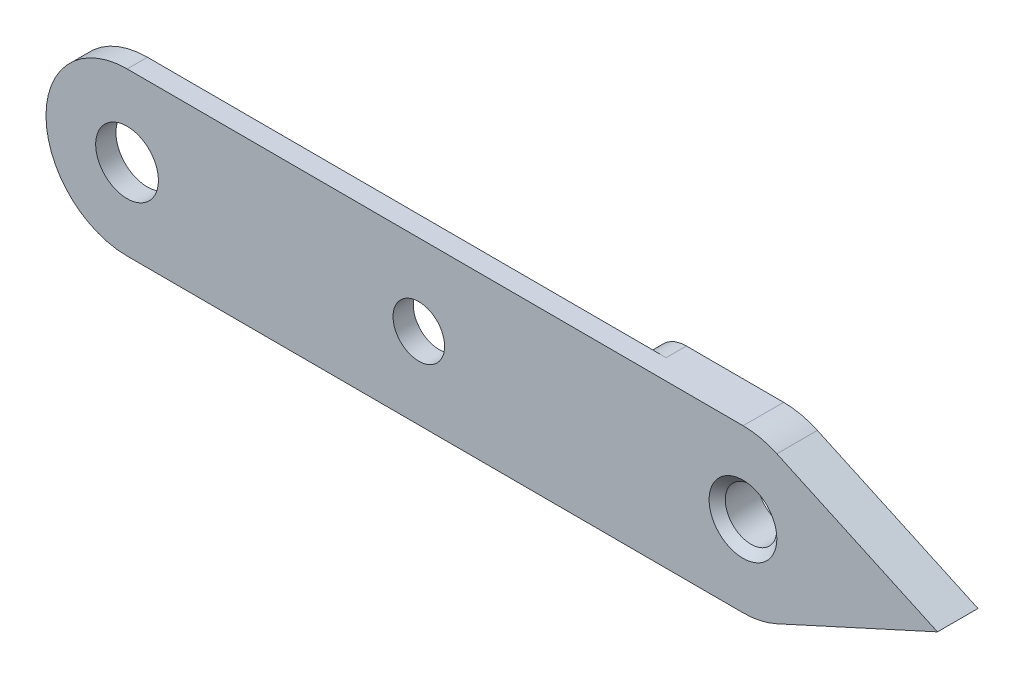
SolidWorks part; units mm, degrees
ref_plane "Front Plane" through (0, 0, 0) normal (0, 0, 1) x (1, 0, 0)
ref_plane "Top Plane" through (0, 0, 0) normal (0, 1, 0) x (1, 0, 0)
ref_plane "Right Plane" through (0, 0, 0) normal (1, 0, 0) x (0, 0, -1)
sketch "Sketch2" plane through (0, 0, -44.7) normal (0, 0, 1) x (1, 0, 0)
  line L0 (-22.86, 0.0379) -> (25.4, -0.0421) construction
  line L1 (-22.8705, -6.3121) -> (25.3894, -6.3921)
  line L2 (-22.8494, 6.3879) -> (25.4105, 6.3079)
  arc A0 (-22.8705, -6.3121) -> (-22.8494, 6.3879) centre (-22.86, 0.0379) cw
  arc A1 (25.3894, -6.3921) -> (25.4105, 6.3079) centre (25.4, -0.0421) ccw
  circle A2 centre (25.4, -0.0421) radius 0.635
  circle A3 centre (0, 0) radius 1.5875
  circle A4 centre (-22.86, 0.0379) radius 0.635
  dimension "D3" = 1.27
  dimension "D4" = 3.175
  dimension "D1" = 6.35
  dimension "D2" = 6.35
extrude "Boss-Extrude1" add sketch "Sketch2" along normal blind 1.5875
hole_wizard "#10 (0.1935) Diameter Hole1" positions "Sketch4" profile "Sketch3" hole size "#10" standard "ANSI Inch" end condition through all
sketch "Sketch4" plane through (0, 0, -43.1125) normal (0, 0, 1) x (1, 0, 0)
  point P0 (-22.86, 0.0379)
sketch "Sketch3" plane through (-22.86, 0.0379, -43.1125) normal (1, 0, 0) x (0, -1, 0)
  line L0 (0, 0) -> (0, 1.5875)
  line L1 (0, 1.5875) -> (2.4574, 1.5875)
  line L2 (2.4574, 1.5875) -> (2.4574, 0)
  line L5 (2.4574, 0) -> (0, 0)
  line L11 (0, -6.35) -> (0, 107.95) construction
  dimension "Thru Hole Dia." = 4.9149
  dimension "Thru Hole Depth" = 1.5875
sketch "Sketch5" plane through (0, 0, -44.7) normal (0, 0, -1) x (-1, 0, 0)
  line L0 (-25.3894, -6.3921) -> (-17.7694, -6.3795)
  line L1 (22.8705, -6.3121) -> (-25.3894, -6.3921) construction
  line L2 (-15.2337, -3.8353) -> (-15.2463, 3.7847)
  line L3 (-17.7905, 6.3205) -> (-25.4105, 6.3079)
  line L4 (-25.4105, 6.3079) -> (22.8494, 6.3879) construction
  line L5 (-17.7737, -3.8395) -> (-17.7694, -6.3795) construction
  line L6 (-17.7737, -3.8395) -> (-15.2337, -3.8353) construction
  arc A1 (-17.7694, -6.3795) -> (-15.2337, -3.8353) centre (-17.7737, -3.8395) ccw
  arc A2 (-15.2463, 3.7847) -> (-17.7905, 6.3205) centre (-17.7863, 3.7805) ccw
  arc A3 (-25.4105, 6.3079) -> (-25.3894, -6.3921) centre (-25.4, -0.0421) ccw construction
  arc A4 (-25.4105, 6.3079) -> (-25.3894, -6.3921) centre (-25.4, -0.0421) ccw
  dimension "D1" = 7.62
  dimension "D2" = 7.62
extrude "Boss-Extrude2" add sketch "Sketch5" along normal blind 1.5875
hole_wizard "#10-32 Tapped Hole1" positions "Sketch7" profile "Sketch6" tap size "#10-32" standard "ANSI Inch"
sketch "Sketch7" plane through (0, 0, -43.1125) normal (0, 0, 1) x (1, 0, 0)
  point P0 (25.4, -0.0421)
sketch "Sketch6" plane through (25.4, -0.0421, -43.1125) normal (1, 0, 0) x (0, -1, 0)
  line L0 (0, 0) -> (0, 10.6113)
  line L1 (0, 10.6113) -> (2.0193, 9.398)
  line L2 (2.0193, 9.398) -> (2.0193, 0.635)
  line L3 (2.0193, 0.635) -> (2.6543, 0)
  line L5 (2.6543, 0) -> (0, 0)
  line L6 (-2.0193, 0.635) -> (-2.6543, 0) construction
  line L10 (0, 10.6113) -> (-2.0193, 9.398) construction
  line L11 (0, -6.35) -> (0, 107.95) construction
  dimension "Tap Drill Dia." = 4.0386
  dimension "Tap Drill Depth" = 9.398
  dimension "Near C'Sink Dia." = 5.3086
  dimension "Near C'Sink Angle" = 90
  dimension "Drill Angle" = 118
cosmetic thread "Hole Thread1" parameters "D1"=3.175, "D2"=4.826
sketch "Sketch8" plane through (0, 0, -43.1125) normal (0, 0, 1) x (1, 0, 0)
  line L0 (28.0554, 5.726) -> (40.6399, -0.0674)
  line L1 (40.6399, -0.0674) -> (28.0362, -5.819)
  line L2 (25.3894, -6.3921) -> (25.4105, 6.3079) construction
  line L3 (25.4, -0.0421) -> (40.6399, -0.0674) construction
  line L4 (28.0554, 5.726) -> (28.0458, -0.0465) construction
  line L5 (28.0458, -0.0465) -> (28.0362, -5.819) construction
  line L6 (-22.8705, -6.3121) -> (25.3894, -6.3921) construction
  arc A1 (28.0362, -5.819) -> (28.0554, 5.726) centre (25.4, -0.0421) ccw
  arc A2 (25.3894, -6.3921) -> (25.4105, 6.3079) centre (25.4, -0.0421) ccw construction
  dimension "D1" = 15.24
extrude "Boss-Extrude3" add sketch "Sketch8" against normal blind 3.175
hole_wizard "#10-32 Tapped Hole2" positions "Sketch10" profile "Sketch9" tap size "#10-32" standard "ANSI Inch" end condition through all
sketch "Sketch10" plane through (0, 0, -43.1125) normal (0, 0, 1) x (1, 0, 0)
  point P0 (0, 0)
sketch "Sketch9" plane through (0, 0, -43.1125) normal (1, 0, 0) x (0, -1, 0)
  line L0 (0, 0) -> (0, 3.175)
  line L1 (0, 3.175) -> (2.0193, 3.175)
  line L2 (2.0193, 3.175) -> (2.0193, 0)
  line L5 (2.0193, 0) -> (0, 0)
  line L11 (0, -6.35) -> (0, 107.95) construction
  dimension "Thru Tap Drill Dia." = 4.0386
  dimension "Thru Tap Drill Depth" = 3.175
cosmetic thread "Hole Thread2" parameters "D1"=1.5875, "D2"=4.826
